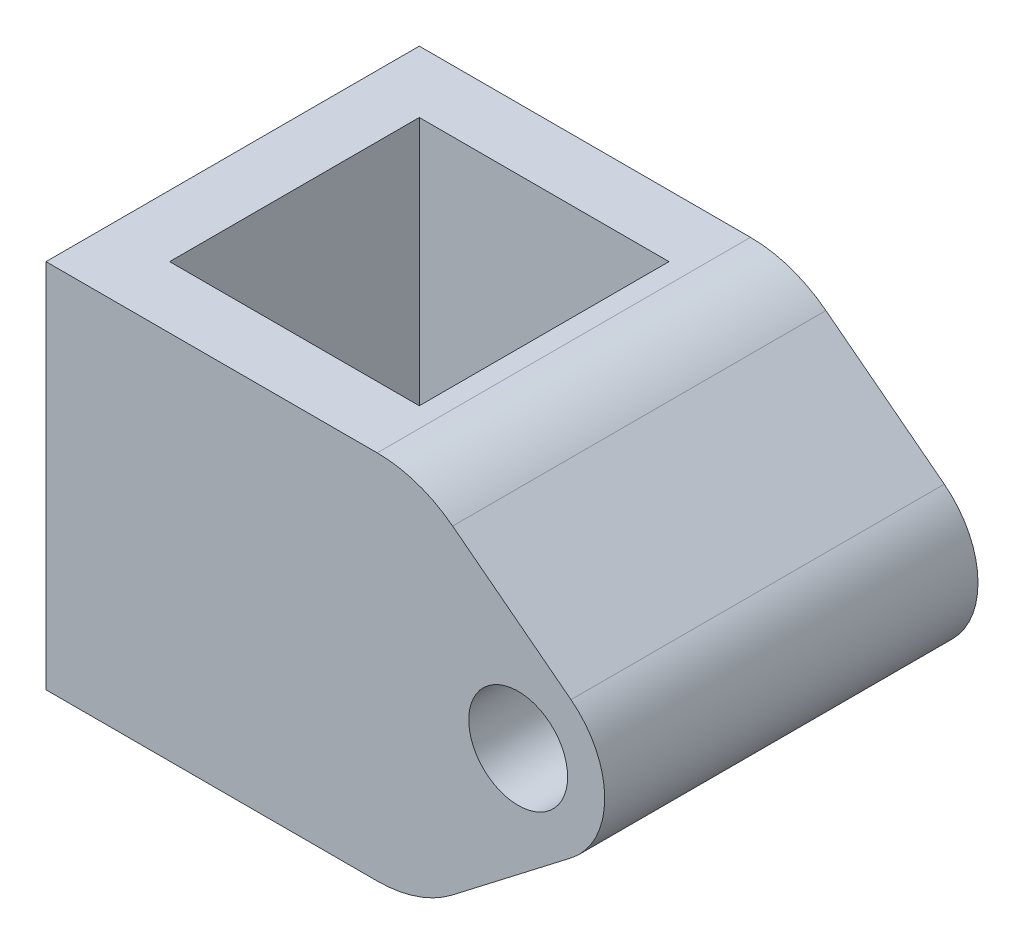
SolidWorks part; units mm, degrees
ref_plane "Front Plane" through (0, 0, 0) normal (0, 0, 1) x (1, 0, 0)
ref_plane "Top Plane" through (0, 0, 0) normal (0, 1, 0) x (1, 0, 0)
ref_plane "Right Plane" through (0, 0, 0) normal (1, 0, 0) x (0, 0, -1)
sketch "Sketch1" plane through (0, 0, 0) normal (0, 1, 0) x (1, 0, 0)
  line L1 (0, 0) -> (20.2, 0)
  line L2 (0, 0) -> (0, 20.2)
  line L3 (0, 20.2) -> (20.2, 20.2)
  line L4 (20.2, 0) -> (20.2, 20.2)
  dimension "D1" = 20.2
extrude "Extrude-Thin1" add sketch "Sketch1" along normal blind 30 thin
sketch "Sketch2" plane through (0, 0, 5) normal (0, 0, 1) x (1, 0, 0)
  line L0 (25.2, 30) -> (37.4722, 20.5451)
  line L1 (25.2, 30) -> (25.2, 0) construction
  line L2 (37.4722, 9.4549) -> (25.2, 0)
  line L3 (33.2, 15) -> (25.2, 15) construction
  line L4 (-5, 30) -> (25.2, 30) construction
  circle A0 centre (33.2, 15) radius 4
  circle A1 centre (33.2, 15) radius 7
  point P7 (40.485, 6.2091)
  point P12 (25.2, 30)
  point P15 (25.2, 0)
  dimension "D1" = 8
  dimension "D2" = 3
  dimension "D3" = 8
extrude "Boss-Extrude1" add sketch "Sketch2" against normal up to surface (30.2 mm away)
fillet "Fillet1" radius 10 2 edges at (25.2, 0, -10.1) (25.2, 30, -10.1)
